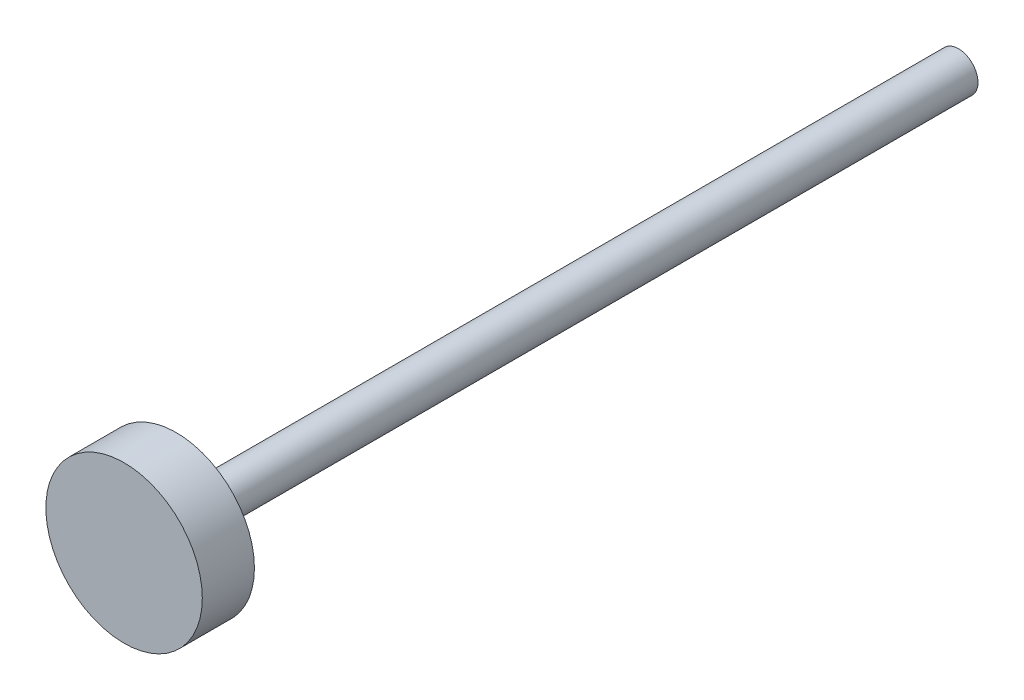
SolidWorks part; units mm, degrees
ref_plane "Front Plane" through (0, 0, 0) normal (0, 0, 1) x (1, 0, 0)
ref_plane "Top Plane" through (0, 0, 0) normal (0, 1, 0) x (1, 0, 0)
ref_plane "Right Plane" through (0, 0, 0) normal (1, 0, 0) x (0, 0, -1)
sketch "Sketch2" plane through (0, 0, 0) normal (1, 0, 0) x (0, 0, -1)
  line L0 (0, 0) -> (0, -1.5)
  line L1 (0, -1.5) -> (-60, -1.5)
  line L2 (-60, -1.5) -> (-60, -6)
  line L3 (-60, -6) -> (-64, -6)
  line L4 (-64, -6) -> (-64, 0)
  line L9 (-64, 0) -> (0, 0)
  dimension "D1" = 1.5
  dimension "D2" = 6
  dimension "D3" = 4
  dimension "D4" = 60
revolve "Revolve1" add sketch "Sketch2" angle 360 about L9
